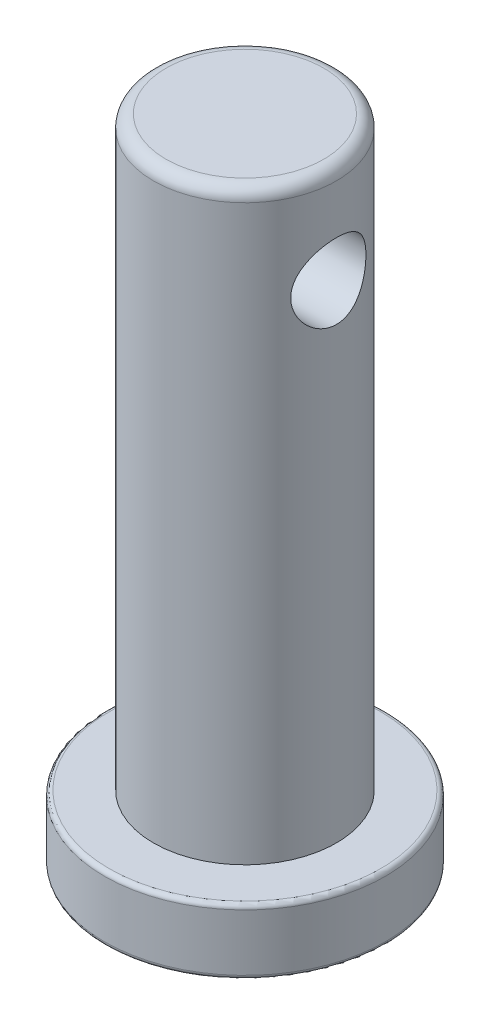
SolidWorks part; units mm, degrees
ref_plane "Front Plane" through (0, 0, 0) normal (0, 0, 1) x (1, 0, 0)
ref_plane "Top Plane" through (0, 0, 0) normal (0, 1, 0) x (1, 0, 0)
ref_plane "Right Plane" through (0, 0, 0) normal (1, 0, 0) x (0, 0, -1)
sketch "Sketch1" plane through (0, 0, 0) normal (0, 1, 0) x (1, 0, 0)
  circle A0 centre (0, 0) radius 7.112
  dimension "D1" = 14.224
extrude "Boss-Extrude1" add sketch "Sketch1" along normal blind 33.02
sketch "Sketch2" plane through (0, 33.02, 0) normal (0, 1, 0) x (1, 0, 0)
  circle A0 centre (0, 0) radius 4.6355
  dimension "D1" = 9.271
extrude "Cut-Extrude1" cut sketch "Sketch2" against normal blind 29.6926 flip side to cut
sketch "Sketch3" plane through (0, 0, 0) normal (1, 0, 0) x (0, 0, -1)
  line L0 (4.6355, 33.02) -> (-4.6355, 33.02) construction
  circle A0 centre (0, 27.9908) radius 1.905
  point P2 (0, 0)
  dimension "D1" = 3.81
  dimension "D2" = 5.0292
extrude "Cut-Extrude2" cut sketch "Sketch3" against normal through all both and the other way through all
sketch "Sketch4" plane through (0, 0, 0) normal (0, -1, 0) x (1, 0, 0)
  text T0 "AF"
extrude "Boss-Extrude2" add sketch "Sketch4" along normal blind 0.254
fillet "Fillet1" radius 0.2286 2 edges at (0, 3.3274, 7.112) (0, 0, 7.112)
fillet "Fillet2" radius 0.635 1 edges at (0, 33.02, 4.6355)
